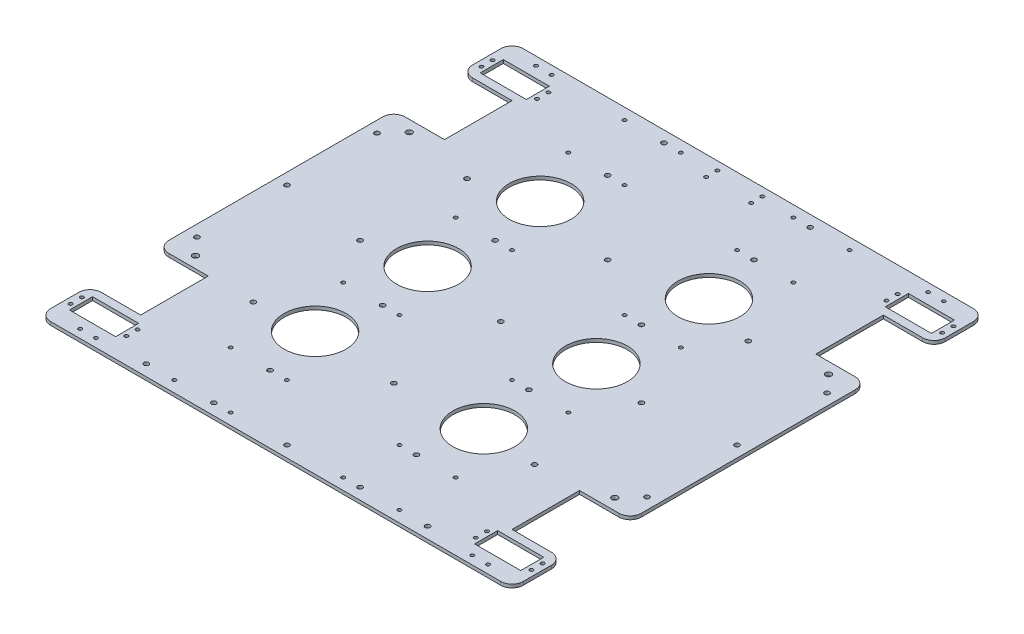
SolidWorks part; units mm, degrees
material "1060 合金"
ref_plane "前视基准面" through (0, 0, 0) normal (0, 0, 1) x (1, 0, 0)
ref_plane "上视基准面" through (0, 0, 0) normal (0, 1, 0) x (1, 0, 0)
ref_plane "右视基准面" through (0, 0, 0) normal (1, 0, 0) x (0, 0, -1)
other "Configuration Table"
sketch "草图2" plane through (0, 0, 0) normal (0, 1, 0) x (1, 0, 0)
  line L1 (210, 210) -> (-210, 210)
  line L2 (210, 210) -> (210, -210)
  line L3 (210, -210) -> (-210, -210)
  line L4 (-210, 210) -> (-210, -210)
  line L5 (210, 210) -> (-210, -210) construction
  line L6 (210, -210) -> (-210, 210) construction
  point P0 (0, 0)
  dimension "D1" = 420
  dimension "D2" = 420
extrude "凸台-拉伸1" add sketch "草图2" along normal blind 3
sketch "草图3" plane through (0, 0, 0) normal (0, 1, 0) x (1, 0, 0)
  line L0 (-210, 210) -> (-210, -210) construction
  line L1 (180, -182.5) -> (-180, -182.5) construction
  line L2 (180, -182.5) -> (180, 182.5) construction
  line L3 (180, 182.5) -> (-180, 182.5) construction
  line L4 (-180, -182.5) -> (-180, 182.5) construction
  line L5 (180, -182.5) -> (-180, 182.5) construction
  line L6 (180, 182.5) -> (-180, -182.5) construction
  line L7 (-159.5, 192.75) -> (-200.5, 192.75)
  line L8 (-159.5, 192.75) -> (-159.5, 172.25)
  line L9 (-159.5, 172.25) -> (-200.5, 172.25)
  line L10 (-200.5, 192.75) -> (-200.5, 172.25)
  line L11 (-159.5, 192.75) -> (-200.5, 172.25) construction
  line L12 (-159.5, 172.25) -> (-200.5, 192.75) construction
  line L13 (-155.25, 187.5) -> (-204.75, 187.5) construction
  line L14 (-155.25, 187.5) -> (-155.25, 177.5) construction
  line L15 (-155.25, 177.5) -> (-204.75, 177.5) construction
  line L16 (-204.75, 187.5) -> (-204.75, 177.5) construction
  line L17 (-155.25, 187.5) -> (-204.75, 177.5) construction
  line L18 (-155.25, 177.5) -> (-204.75, 187.5) construction
  line L20 (210, 210) -> (-210, 210) construction
  line L22 (187.5, -135) -> (-187.5, -135) construction
  line L23 (187.5, -135) -> (187.5, 135) construction
  line L24 (187.5, 135) -> (-187.5, 135) construction
  line L25 (-187.5, -135) -> (-187.5, 135) construction
  line L26 (187.5, -135) -> (-187.5, 135) construction
  line L27 (187.5, 135) -> (-187.5, -135) construction
  line L28 (-165, 165) -> (-210, 165)
  line L29 (-165, 165) -> (-165, 105)
  line L30 (-165, 105) -> (-210, 105)
  line L31 (-210, 165) -> (-210, 105)
  line L32 (-165, 165) -> (-210, 105) construction
  line L33 (-165, 105) -> (-210, 165) construction
  circle A0 centre (-204.75, 187.5) radius 1.6
  circle A1 centre (-204.75, 177.5) radius 1.6
  circle A2 centre (-155.25, 187.5) radius 1.6
  circle A3 centre (-155.25, 177.5) radius 1.6
  point P0 (0, 0)
  point P22 (0, 0)
  dimension "D5" = 3.2
  dimension "D1" = 41
  dimension "D2" = 20.5
  dimension "D3" = 49.5
  dimension "D4" = 10
  dimension "D6" = 30
  dimension "D7" = 27.5
  dimension "D8" = 60
  dimension "D9" = 45
  dimension "D10" = 75
  dimension "D12" = 270
  dimension "D13" = 7.25
extrude "切除-拉伸1" cut sketch "草图3" along normal through all
mirror "镜向2" about plane through (0, 0, 0) normal (1, 0, 0) of "切除-拉伸1" second plane through (0, 0, 0) second plane normal (0, 0, 1)
sketch "草图5" plane through (0, 0, 0) normal (0, 1, 0) x (1, 0, 0)
  line L0 (65, 0) -> (-65, 0) construction
  circle A1 centre (-65, 0) radius 2.15
  circle A2 centre (65, 0) radius 2.15
  point P5 (0, 0)
  dimension "D1" = 4.3
  dimension "D2" = 130
sketch "草图7" plane through (0, 0, 0) normal (0, 1, 0) x (1, 0, 0)
  line L0 (210, 210) -> (-210, 210) construction
  line L1 (186.25, 95) -> (-186.25, 95) construction
  line L2 (186.25, 95) -> (186.25, -95) construction
  line L3 (186.25, -95) -> (-186.25, -95) construction
  line L4 (-186.25, 95) -> (-186.25, -95) construction
  line L5 (186.25, 95) -> (-186.25, -95) construction
  line L6 (186.25, -95) -> (-186.25, 95) construction
  line L7 (-210, 105) -> (-165, 105) construction
  circle A0 centre (-186.25, 95) radius 2.65
  circle A1 centre (-186.25, -95) radius 2.65
  circle A2 centre (186.25, -95) radius 2.65
  circle A3 centre (186.25, 95) radius 2.65
  point P0 (0, 0)
  dimension "D3" = 5.3
  dimension "D1" = 372.5
  dimension "D2" = 10
  dimension "D4" = 210
  dimension "D5" = 190
extrude "切除-拉伸5" cut sketch "草图7" along normal through all
extrude "切除-拉伸8" cut sketch "草图5" along normal through all
pattern_linear "阵列(线性)4" count 5 spacing 50 along (0, 0, 1) count 5 spacing 50 along (0, 0, -1) of "切除-拉伸8"
sketch "草图6" plane through (0, 0, 0) normal (0, 1, 0) x (1, 0, 0)
  line L0 (0, 0) -> (0, -200) construction
  line L1 (-210, -210) -> (210, -210) construction
  line L2 (125, -200) -> (-125, -200) construction
  circle A2 centre (-125, -200) radius 2.15
  circle A3 centre (125, -200) radius 2.15
  circle A4 centre (0, -200) radius 2.15
  point P4 (0, -200)
  point P10 (0, -200)
  dimension "D2" = 10
  dimension "D1" = 4.3
  dimension "D3" = 250
extrude "切除-拉伸9" cut sketch "草图6" along normal through all
pattern_linear "阵列(线性)5" count 4 spacing 95 along (0, 0, -1) of "切除-拉伸9"
sketch "草图9" plane through (0, 0, 0) normal (0, 1, 0) x (1, 0, 0)
  line L0 (0, 0) -> (0, 50000) construction
  line L1 (-50, -200) -> (50, -200) construction
  line L2 (-100, -200) -> (100, -200) construction
  line L3 (-210, -210) -> (210, -210) construction
  circle A0 centre (-100, -200) radius 1.6
  circle A1 centre (-50, -200) radius 1.6
  circle A2 centre (50, -200) radius 1.6
  circle A3 centre (100, -200) radius 1.6
  point P6 (0, -200)
  point P9 (0, -200)
  dimension "D4" = 3.2
  dimension "D1" = 100
  dimension "D2" = 200
  dimension "D3" = 10
extrude "切除-拉伸7" cut sketch "草图9" along normal through all
pattern_linear "阵列(线性)3" count 9 spacing 50 along (0, 0, -1) of "切除-拉伸7"
sketch "草图10" plane through (0, 0, 0) normal (0, 1, 0) x (1, 0, 0)
  line L1 (75, 100) -> (-75, 100) construction
  line L2 (75, 100) -> (75, -100) construction
  line L3 (75, -100) -> (-75, -100) construction
  line L4 (-75, 100) -> (-75, -100) construction
  line L5 (75, 100) -> (-75, -100) construction
  line L6 (75, -100) -> (-75, 100) construction
  circle A6 centre (-75, 100) radius 27.5
  circle A7 centre (75, 100) radius 27.5
  circle A8 centre (75, 0) radius 27.5
  circle A9 centre (-75, 0) radius 27.5
  circle A10 centre (-75, -100) radius 27.5
  circle A11 centre (75, -100) radius 27.5
  point P0 (0, 0)
  dimension "D1" = 55
  dimension "D2" = 200
  dimension "D3" = 150
extrude "切除-拉伸10" cut sketch "草图10" along normal through all
sketch "草图8" plane through (0, 0, 0) normal (0, 1, 0) x (1, 0, 0)
  line L0 (210, 210) -> (-210, 210) construction
  line L1 (200, 80) -> (-200, 80) construction
  line L2 (200, 80) -> (200, -80) construction
  line L3 (200, -80) -> (-200, -80) construction
  line L4 (-200, 80) -> (-200, -80) construction
  line L5 (200, 80) -> (-200, -80) construction
  line L6 (200, -80) -> (-200, 80) construction
  line L7 (-210, 210) -> (-210, 165) construction
  line L8 (181.25, 202.5) -> (-181.25, 202.5) construction
  line L9 (181.25, 202.5) -> (181.25, -202.5) construction
  line L10 (181.25, -202.5) -> (-181.25, -202.5) construction
  line L11 (-181.25, 202.5) -> (-181.25, -202.5) construction
  line L12 (181.25, 202.5) -> (-181.25, -202.5) construction
  line L13 (181.25, -202.5) -> (-181.25, 202.5) construction
  line L15 (167.25, -202.5) -> (-167.25, -202.5) construction
  line L16 (167.25, -202.5) -> (167.25, 202.5) construction
  line L17 (167.25, 202.5) -> (-167.25, 202.5) construction
  line L18 (-167.25, -202.5) -> (-167.25, 202.5) construction
  line L19 (167.25, -202.5) -> (-167.25, 202.5) construction
  line L20 (167.25, 202.5) -> (-167.25, -202.5) construction
  circle A0 centre (-200, 80) radius 2.15
  circle A1 centre (-200, -80) radius 2.15
  circle A2 centre (-200, 0) radius 2.15
  circle A3 centre (200, 0) radius 2.15
  circle A4 centre (200, 80) radius 2.15
  circle A5 centre (200, -80) radius 2.15
  circle A6 centre (-167.25, 202.5) radius 1.6
  circle A9 centre (-181.25, 202.5) radius 1.6
  circle A10 centre (181.25, 202.5) radius 1.6
  circle A11 centre (181.25, -202.5) radius 1.6
  circle A12 centre (-181.25, -202.5) radius 1.6
  circle A13 centre (167.25, 202.5) radius 1.6
  circle A14 centre (-167.25, -202.5) radius 1.6
  circle A15 centre (167.25, -202.5) radius 1.6
  point P0 (0, 0)
  point P17 (0, 0)
  point P27 (0, 0)
  dimension "D3" = 4.3
  dimension "D6" = 28.75
  dimension "D7" = 3.2
  dimension "D1" = 400
  dimension "D2" = 160
  dimension "D4" = 210
  dimension "D5" = 7.5
  dimension "D8" = 14
extrude "切除-拉伸6" cut sketch "草图8" along normal through all
fillet "圆角1" radius 10 12 edges at (210, 1.5, -105) (210, 1.5, -165) (210, 1.5, 165) (210, 1.5, 105) (-210, 1.5, -165) (-210, 1.5, -105) (-210, 1.5, 105) (-210, 1.5, 165) (-210, 1.5, -210) (210, 1.5, -210) (210, 1.5, 210) (-210, 1.5, 210)
sketch "草图11" plane through (0, 3, 0) normal (0, 1, 0) x (1, 0, 0)
  line L0 (200, 210) -> (-200, 210) construction
  line L1 (-20, 202.5) -> (20, 202.5) construction
  line L2 (-20, 202.5) -> (-20, 192.5) construction
  line L3 (-20, 192.5) -> (20, 192.5) construction
  line L4 (20, 202.5) -> (20, 192.5) construction
  line L5 (-20, 202.5) -> (20, 192.5) construction
  line L6 (-20, 192.5) -> (20, 202.5) construction
  circle A0 centre (-20, 202.5) radius 1.6
  circle A1 centre (20, 202.5) radius 1.6
  circle A2 centre (-20, 192.5) radius 1.6
  circle A3 centre (20, 192.5) radius 1.6
  point P0 (0, 197.5)
  dimension "D4" = 3.2
  dimension "D5" = 3.2
  dimension "D6" = 3.2
  dimension "D7" = 3.2
  dimension "D1" = 10
  dimension "D2" = 40
  dimension "D3" = 7.5
extrude "切除-拉伸11" cut sketch "草图11" against normal blind 5
